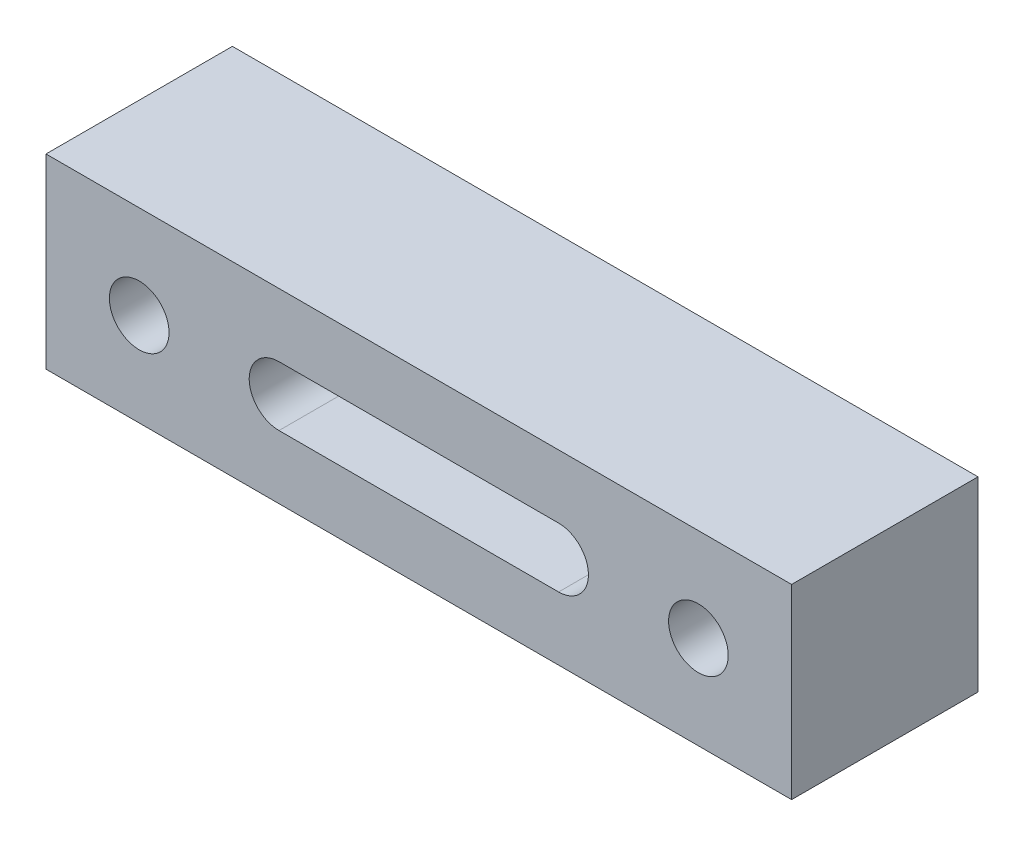
SolidWorks part; units mm, degrees
ref_plane "前视基准面" through (0, 0, 0) normal (0, 0, 1) x (1, 0, 0)
ref_plane "上视基准面" through (0, 0, 0) normal (0, 1, 0) x (1, 0, 0)
ref_plane "右视基准面" through (0, 0, 0) normal (1, 0, 0) x (0, 0, -1)
other "Configuration Table"
sketch "草图1" plane through (0, 0, 0) normal (0, 0, 1) x (1, 0, 0)
  line L0 (8.1818, 13.5885) -> (-21.8182, 13.5885) construction
  line L1 (-21.8182, 18.5885) -> (8.1818, 18.5885) construction
  line L2 (-21.8182, 18.5885) -> (-21.8182, 8.5885) construction
  line L3 (-21.8182, 8.5885) -> (8.1818, 8.5885) construction
  line L4 (8.1818, 18.5885) -> (8.1818, 8.5885) construction
  line L5 (-14.3182, 13.5885) -> (0.6818, 13.5885) construction
  line L6 (-26.8182, 18.5885) -> (13.1818, 18.5885)
  line L7 (-26.8182, 18.5885) -> (-26.8182, 8.5885)
  line L8 (-26.8182, 8.5885) -> (13.1818, 8.5885)
  line L9 (13.1818, 18.5885) -> (13.1818, 8.5885)
  line L11 (-14.3182, 15.1885) -> (0.6818, 15.1885)
  line L12 (-14.3182, 11.9885) -> (0.6818, 11.9885)
  circle A0 centre (-21.8182, 13.5885) radius 1.6
  circle A1 centre (8.1818, 13.5885) radius 1.6
  arc A2 (-14.3182, 15.1885) -> (-14.3182, 11.9885) centre (-14.3182, 13.5885) ccw
  arc A3 (0.6818, 11.9885) -> (0.6818, 15.1885) centre (0.6818, 13.5885) ccw
  point P12 (-6.8182, 13.5885)
  point P13 (-6.8182, 18.5885)
  point P18 (-6.8182, 13.5885)
  dimension "D3" = 3.2
  dimension "D1" = 30
  dimension "D2" = 10
  dimension "D4" = 40
  dimension "D5" = 15
extrude "凸台-拉伸1" add sketch "草图1" along normal blind 10
sketch "草图2" plane through (0, 0, 0) normal (0, 0, -1) x (-1, 0, 0)
  line L0 (-2.2818, 13.5885) -> (15.9182, 13.5885) construction
  line L1 (-3.1818, 16.5885) -> (16.8182, 16.5885)
  line L2 (-3.1818, 16.5885) -> (-3.1818, 10.5885)
  line L3 (-3.1818, 10.5885) -> (16.8182, 10.5885)
  line L4 (16.8182, 16.5885) -> (16.8182, 10.5885)
  arc A0 (-0.6818, 15.1885) -> (-0.6818, 11.9885) centre (-0.6818, 13.5885) ccw construction
  arc A1 (14.3182, 11.9885) -> (14.3182, 15.1885) centre (14.3182, 13.5885) ccw construction
  point P12 (6.8182, 13.5885)
  point P13 (6.8182, 16.5885)
  point P14 (-3.1818, 13.5885)
  dimension "D1" = 20
  dimension "D2" = 6
extrude "切除-拉伸1" cut sketch "草图2" against normal blind 6
